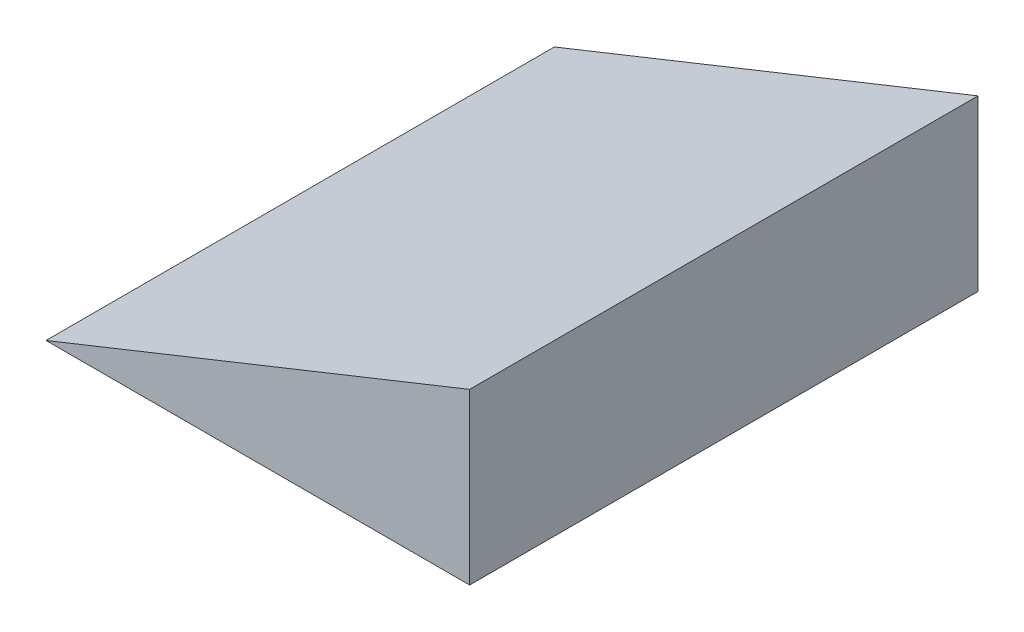
SolidWorks part; units mm, degrees
ref_plane "前视基准面" through (0, 0, 0) normal (0, 0, 1) x (1, 0, 0)
ref_plane "上视基准面" through (0, 0, 0) normal (0, 1, 0) x (1, 0, 0)
ref_plane "右视基准面" through (0, 0, 0) normal (1, 0, 0) x (0, 0, -1)
other "Configuration Table"
sketch "草图1" plane through (0, 0, 0) normal (0, 1, 0) x (1, 0, 0)
  line L1 (-103.0192, 125.4497) -> (146.9808, 125.4497)
  line L2 (-103.0192, 125.4497) -> (-103.0192, -174.5503)
  line L3 (-103.0192, -174.5503) -> (146.9808, -174.5503)
  line L4 (146.9808, 125.4497) -> (146.9808, -174.5503)
  dimension "D1" = 300
  dimension "D2" = 250
extrude "凸台-拉伸1" add sketch "草图1" along normal blind 100
sketch "草图2" plane through (0, 0, 174.5503) normal (0, 0, 1) x (1, 0, 0)
  line L0 (-103.0192, 0) -> (146.9808, 100)
  line L1 (146.9808, 100) -> (-103.0192, 100)
  line L2 (-103.0192, 100) -> (-103.0192, 0)
extrude "切除-拉伸1" cut sketch "草图2" against normal up to next
